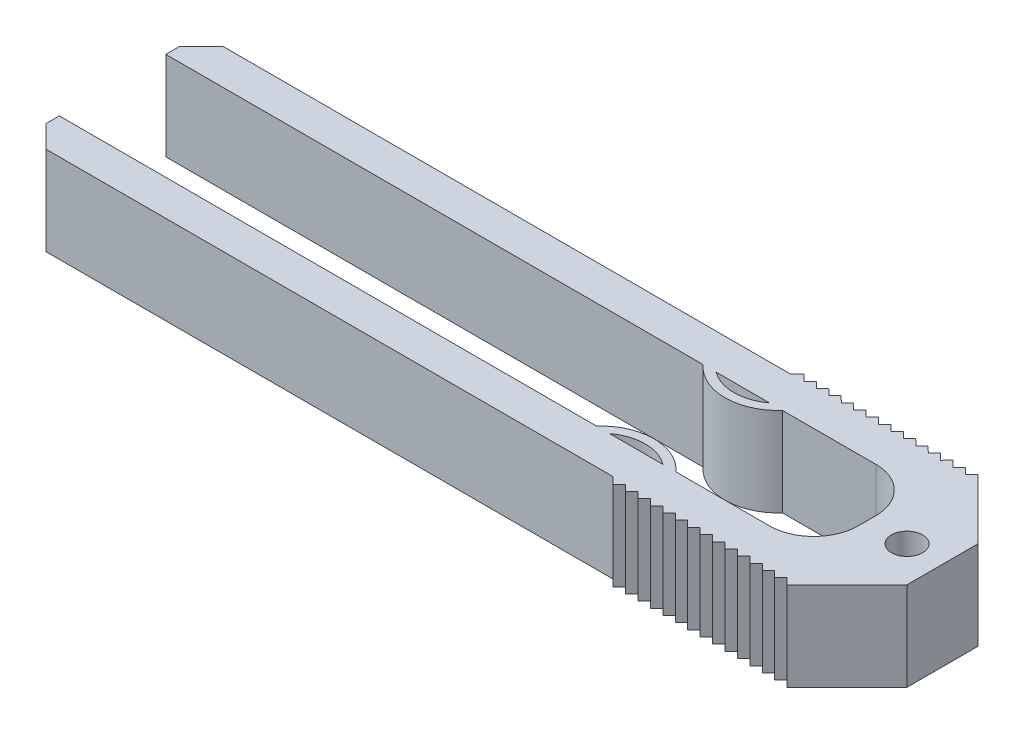
SolidWorks part; units mm, degrees
ref_plane "Front Plane" through (0, 0, 0) normal (0, 0, 1) x (1, 0, 0)
ref_plane "Top Plane" through (0, 0, 0) normal (0, 1, 0) x (1, 0, 0)
ref_plane "Right Plane" through (0, 0, 0) normal (1, 0, 0) x (0, 0, -1)
sketch "Sketch1" plane through (0, 0, 0) normal (0, 1, 0) x (1, 0, 0)
  line L0 (-90, -12) -> (-90, -20)
  line L1 (-90, 20) -> (90, 20)
  line L2 (-90, 20) -> (-90, 12)
  line L3 (-90, -20) -> (90, -20)
  line L4 (90, 20) -> (90, -20)
  line L5 (-90, 20) -> (90, -20) construction
  line L6 (-90, -20) -> (90, 20) construction
  line L7 (-90, 12) -> (80, 12)
  line L9 (-90, -12) -> (80, -12)
  line L10 (80, 12) -> (80, -12)
  point P0 (0, 0)
  dimension "D1" = 180
  dimension "D2" = 24
  dimension "D3" = 8
  dimension "D4" = 8
  dimension "D5" = 10
extrude "Boss-Extrude1" add sketch "Sketch1" along normal blind 20
fillet "Fillet1" radius 10 2 edges at (80, 10, 12) (80, 10, -12)
chamfer "Chamfer1" distance 5 angle 45 2 edges at (90, 10, 20) (90, 10, -20)
chamfer "Chamfer2" distance 5 angle 45 2 edges at (-90, 10, -20) (-90, 10, 20)
sketch "Sketch2" plane through (0, 20, 0) normal (0, 1, 0) x (1, 0, 0)
  line L0 (85, 20) -> (-85, 20) construction
  line L1 (-85, -20) -> (85, -20) construction
  line L2 (80, 2) -> (80, -2) construction
  line L3 (31.0557, -12) -> (34, -12)
  line L4 (70, -12) -> (-90, -12) construction
  line L5 (31.0557, 12) -> (34, 12)
  line L6 (-90, 12) -> (70, 12) construction
  line L7 (46, -12) -> (48.9443, -12)
  line L8 (46, 12) -> (48.9443, 12)
  arc A0 (31.0557, 12) -> (48.9443, 12) centre (40, 20) ccw
  arc A1 (48.9443, -12) -> (31.0557, -12) centre (40, -20) ccw
  arc A2 (34, 12) -> (46, 12) centre (40, 20) ccw
  arc A3 (46, -12) -> (34, -12) centre (40, -20) ccw
  dimension "D1" = 24
  dimension "D2" = 24
  dimension "D3" = 40
  dimension "D4" = 40
  dimension "D5" = 2
  dimension "D6" = 2
extrude "Boss-Extrude2" add sketch "Sketch2" against normal blind 20
sketch "Sketch3" plane through (0, 20, 0) normal (0, 1, 0) x (1, 0, 0)
  line L0 (85, 20) -> (83.4689, 21.5)
  line L1 (83.4689, 21.5) -> (81.9994, 20)
  line L2 (85, 20) -> (-85, 20) construction
  line L3 (81.9994, 20) -> (85, 20)
  line L4 (80.6689, 21.5) -> (79.1994, 20)
  line L5 (79.1994, 20) -> (82.2, 20)
  line L6 (82.2, 20) -> (80.6689, 21.5)
  line L7 (77.8689, 21.5) -> (76.3994, 20)
  line L8 (76.3994, 20) -> (79.4, 20)
  line L9 (79.4, 20) -> (77.8689, 21.5)
  line L10 (75.0689, 21.5) -> (73.5994, 20)
  line L11 (73.5994, 20) -> (76.6, 20)
  line L12 (76.6, 20) -> (75.0689, 21.5)
  line L13 (72.2689, 21.5) -> (70.7994, 20)
  line L14 (70.7994, 20) -> (73.8, 20)
  line L15 (73.8, 20) -> (72.2689, 21.5)
  line L16 (69.4689, 21.5) -> (67.9994, 20)
  line L17 (67.9994, 20) -> (71, 20)
  line L18 (71, 20) -> (69.4689, 21.5)
  line L19 (66.6689, 21.5) -> (65.1994, 20)
  line L20 (65.1994, 20) -> (68.2, 20)
  line L21 (68.2, 20) -> (66.6689, 21.5)
  line L22 (63.8689, 21.5) -> (62.3994, 20)
  line L23 (62.3994, 20) -> (65.4, 20)
  line L24 (65.4, 20) -> (63.8689, 21.5)
  line L25 (61.0689, 21.5) -> (59.5994, 20)
  line L26 (59.5994, 20) -> (62.6, 20)
  line L27 (62.6, 20) -> (61.0689, 21.5)
  line L28 (58.2689, 21.5) -> (56.7994, 20)
  line L29 (56.7994, 20) -> (59.8, 20)
  line L30 (59.8, 20) -> (58.2689, 21.5)
  line L31 (55.4689, 21.5) -> (53.9994, 20)
  line L32 (53.9994, 20) -> (57, 20)
  line L33 (57, 20) -> (55.4689, 21.5)
  line L34 (52.6689, 21.5) -> (51.1994, 20)
  line L35 (51.1994, 20) -> (54.2, 20)
  line L36 (54.2, 20) -> (52.6689, 21.5)
  line L37 (49.8689, 21.5) -> (48.3994, 20)
  line L38 (48.3994, 20) -> (51.4, 20)
  line L39 (51.4, 20) -> (49.8689, 21.5)
  line L40 (47.0689, 21.5) -> (45.5994, 20)
  line L41 (45.5994, 20) -> (48.6, 20)
  line L42 (48.6, 20) -> (47.0689, 21.5)
  line L43 (44.2689, 21.5) -> (42.7994, 20)
  line L44 (42.7994, 20) -> (45.8, 20)
  line L45 (45.8, 20) -> (44.2689, 21.5)
  line M6 (85, 20) -> (-85, 20)
  dimension "D1" = 1.5
  dimension "D2" = 15
extrude "Boss-Extrude3" add sketch "Sketch3" against normal blind 20 contours L6 L0 L1 M6 | L9 L1 L6 L4 M6 | L12 L4 L9 L7 M6 | L15 L7 L12 L10 M6 | L18 L10 L15 L13 M6 | L21 L13 L18 L16 M6 | L24 L16 L21 L19 M6 | L27 L19 L24 L22 M6 | L30 L22 L27 L25 M6 | L33 L25 L30 L28 M6 | L36 L28 L33 L31 M6 | L40 L45 L43 M6 | L45 L37 L42 L40 M6 | L42 L34 L39 L37 M6 | L39 L31 L36 L34 M6 | L41 L45 L40 | L38 L42 L37 | L35 L39 L34 | L32 L36 L31 | L29 L33 L28 | L26 L30 L25 | L23 L27 L22 | L20 L24 L19 | L17 L21 L16 | L14 L18 L13 | L11 L15 L10
sketch "Sketch4" plane through (0, 20, 0) normal (0, 1, 0) x (1, 0, 0)
  line L0 (85, -20) -> (83.5, -21.5)
  line L1 (83.5, -21.5) -> (82, -20)
  line L2 (-85, -20) -> (85, -20) construction
  line L3 (82, -20) -> (85, -20)
  line L4 (80.7, -21.5) -> (79.2, -20)
  line L5 (82.2, -20) -> (80.7, -21.5)
  line L6 (79.2, -20) -> (82.2, -20)
  line L7 (77.9, -21.5) -> (76.4, -20)
  line L8 (79.4, -20) -> (77.9, -21.5)
  line L9 (76.4, -20) -> (79.4, -20)
  line L10 (75.1, -21.5) -> (73.6, -20)
  line L11 (76.6, -20) -> (75.1, -21.5)
  line L12 (73.6, -20) -> (76.6, -20)
  line L13 (72.3, -21.5) -> (70.8, -20)
  line L14 (73.8, -20) -> (72.3, -21.5)
  line L15 (70.8, -20) -> (73.8, -20)
  line L16 (69.5, -21.5) -> (68, -20)
  line L17 (71, -20) -> (69.5, -21.5)
  line L18 (68, -20) -> (71, -20)
  line L19 (66.7, -21.5) -> (65.2, -20)
  line L20 (68.2, -20) -> (66.7, -21.5)
  line L21 (65.2, -20) -> (68.2, -20)
  line L22 (63.9, -21.5) -> (62.4, -20)
  line L23 (65.4, -20) -> (63.9, -21.5)
  line L24 (62.4, -20) -> (65.4, -20)
  line L25 (61.1, -21.5) -> (59.6, -20)
  line L26 (62.6, -20) -> (61.1, -21.5)
  line L27 (59.6, -20) -> (62.6, -20)
  line L28 (58.3, -21.5) -> (56.8, -20)
  line L29 (59.8, -20) -> (58.3, -21.5)
  line L30 (56.8, -20) -> (59.8, -20)
  line L31 (55.5, -21.5) -> (54, -20)
  line L32 (57, -20) -> (55.5, -21.5)
  line L33 (54, -20) -> (57, -20)
  line L34 (52.7, -21.5) -> (51.2, -20)
  line L35 (54.2, -20) -> (52.7, -21.5)
  line L36 (51.2, -20) -> (54.2, -20)
  line L37 (49.9, -21.5) -> (48.4, -20)
  line L38 (51.4, -20) -> (49.9, -21.5)
  line L39 (48.4, -20) -> (51.4, -20)
  line L40 (47.1, -21.5) -> (45.6, -20)
  line L41 (48.6, -20) -> (47.1, -21.5)
  line L42 (45.6, -20) -> (48.6, -20)
  line L43 (44.3, -21.5) -> (42.8, -20)
  line L44 (45.8, -20) -> (44.3, -21.5)
  line L45 (42.8, -20) -> (45.8, -20)
  dimension "D1" = 1.5
  dimension "D2" = 45
  dimension "D3" = 15
extrude "Boss-Extrude4" add sketch "Sketch4" against normal blind 20 contours L3 L5 L1 L0 | L5 L3 L1 | L6 L8 L4 L5 L1 | L8 L6 L4 | L9 L11 L7 L8 L4 | L12 L14 L10 L11 L7 | L11 L9 L7 | L14 L12 L10 | L15 L17 L13 L14 L10 | L17 L15 L13 | L18 L20 L16 L17 L13 | L21 L23 L19 L20 L16 | L24 L26 L22 L23 L19 | L26 L24 L22 | L27 L29 L25 L26 L22 | L33 L35 L31 L32 L28 | L30 L32 L28 L29 L25 | L32 L30 L28 | L29 L27 L25 | L36 L38 L34 L35 L31 | L39 L41 L37 L38 L34 | L42 L44 L40 L41 L37 | L45 L43 L44 L40 | L38 L36 L34 | L35 L33 L31
sketch "Sketch5" plane through (0, 20, 0) normal (0, 1, 0) x (1, 0, 0)
  line L0 (90, 15) -> (97, 8)
  line L1 (90, -15) -> (97, -8)
  line L2 (97, -8) -> (97, 8)
  line L3 (90, -15) -> (90, 15) construction
  line L4 (90, 15) -> (90, -15)
  line L77 (90, 15) -> (85, 20)
  line L78 (85, 20) -> (83.4689, 21.5)
  line L79 (83.4689, 21.5) -> (82.0976, 20.1003)
  line L80 (82.0976, 20.1003) -> (80.6689, 21.5)
  line L81 (80.6689, 21.5) -> (79.2976, 20.1003)
  line L82 (79.2976, 20.1003) -> (77.8689, 21.5)
  line L83 (77.8689, 21.5) -> (76.4976, 20.1003)
  line L84 (76.4976, 20.1003) -> (75.0689, 21.5)
  line L85 (75.0689, 21.5) -> (73.6976, 20.1003)
  line L86 (73.6976, 20.1003) -> (72.2689, 21.5)
  line L87 (72.2689, 21.5) -> (70.8976, 20.1003)
  line L88 (70.8976, 20.1003) -> (69.4689, 21.5)
  line L89 (69.4689, 21.5) -> (68.0976, 20.1003)
  line L90 (68.0976, 20.1003) -> (66.6689, 21.5)
  line L91 (66.6689, 21.5) -> (65.2976, 20.1003)
  line L92 (65.2976, 20.1003) -> (63.8689, 21.5)
  line L93 (63.8689, 21.5) -> (62.4976, 20.1003)
  line L94 (62.4976, 20.1003) -> (61.0689, 21.5)
  line L95 (61.0689, 21.5) -> (59.6976, 20.1003)
  line L96 (59.6976, 20.1003) -> (58.2689, 21.5)
  line L97 (58.2689, 21.5) -> (56.8976, 20.1003)
  line L98 (56.8976, 20.1003) -> (55.4689, 21.5)
  line L99 (55.4689, 21.5) -> (54.0976, 20.1003)
  line L100 (54.0976, 20.1003) -> (52.6689, 21.5)
  line L101 (52.6689, 21.5) -> (51.2976, 20.1003)
  line L102 (51.2976, 20.1003) -> (49.8689, 21.5)
  line L103 (49.8689, 21.5) -> (48.4976, 20.1003)
  line L104 (48.4976, 20.1003) -> (47.0689, 21.5)
  line L105 (47.0689, 21.5) -> (45.6976, 20.1003)
  line L106 (45.6976, 20.1003) -> (44.2689, 21.5)
  line L107 (44.2689, 21.5) -> (42.7994, 20)
  line L108 (42.7994, 20) -> (-85, 20)
  line L109 (-85, 20) -> (-90, 15)
  line L110 (-90, 15) -> (-90, 12)
  line L111 (-90, 12) -> (31.0557, 12)
  line L112 (48.9443, 12) -> (70, 12)
  line L113 (80, 2) -> (80, -2)
  line L114 (70, -12) -> (48.9443, -12)
  line L115 (31.0557, -12) -> (-90, -12)
  line L116 (-90, -12) -> (-90, -15)
  line L117 (-90, -15) -> (-85, -20)
  line L118 (-85, -20) -> (42.8, -20)
  line L119 (42.8, -20) -> (44.3, -21.5)
  line L120 (44.3, -21.5) -> (45.7, -20.1)
  line L121 (45.7, -20.1) -> (47.1, -21.5)
  line L122 (47.1, -21.5) -> (48.5, -20.1)
  line L123 (48.5, -20.1) -> (49.9, -21.5)
  line L124 (49.9, -21.5) -> (51.3, -20.1)
  line L125 (51.3, -20.1) -> (52.7, -21.5)
  line L126 (52.7, -21.5) -> (54.1, -20.1)
  line L127 (54.1, -20.1) -> (55.5, -21.5)
  line L128 (55.5, -21.5) -> (56.9, -20.1)
  line L129 (56.9, -20.1) -> (58.3, -21.5)
  line L130 (58.3, -21.5) -> (59.7, -20.1)
  line L131 (59.7, -20.1) -> (61.1, -21.5)
  line L132 (61.1, -21.5) -> (62.5, -20.1)
  line L133 (62.5, -20.1) -> (63.9, -21.5)
  line L134 (63.9, -21.5) -> (65.3, -20.1)
  line L135 (65.3, -20.1) -> (66.7, -21.5)
  line L136 (66.7, -21.5) -> (68.1, -20.1)
  line L137 (68.1, -20.1) -> (69.5, -21.5)
  line L138 (69.5, -21.5) -> (70.9, -20.1)
  line L139 (70.9, -20.1) -> (72.3, -21.5)
  line L140 (72.3, -21.5) -> (73.7, -20.1)
  line L141 (73.7, -20.1) -> (75.1, -21.5)
  line L142 (75.1, -21.5) -> (76.5, -20.1)
  line L143 (76.5, -20.1) -> (77.9, -21.5)
  line L144 (77.9, -21.5) -> (79.3, -20.1)
  line L145 (79.3, -20.1) -> (80.7, -21.5)
  line L146 (80.7, -21.5) -> (82.1, -20.1)
  line L147 (82.1, -20.1) -> (83.5, -21.5)
  line L148 (83.5, -21.5) -> (90, -15)
  line L149 (90, -15) -> (90, 15)
  line L150 (90, 15) -> (85, 20)
  line L151 (85, 20) -> (83.4689, 21.5)
  line L152 (83.4689, 21.5) -> (82.0976, 20.1003)
  line L153 (82.0976, 20.1003) -> (80.6689, 21.5)
  line L154 (80.6689, 21.5) -> (79.2976, 20.1003)
  line L155 (79.2976, 20.1003) -> (77.8689, 21.5)
  line L156 (77.8689, 21.5) -> (76.4976, 20.1003)
  line L157 (76.4976, 20.1003) -> (75.0689, 21.5)
  line L158 (75.0689, 21.5) -> (73.6976, 20.1003)
  line L159 (73.6976, 20.1003) -> (72.2689, 21.5)
  line L160 (72.2689, 21.5) -> (70.8976, 20.1003)
  line L161 (70.8976, 20.1003) -> (69.4689, 21.5)
  line L162 (69.4689, 21.5) -> (68.0976, 20.1003)
  line L163 (68.0976, 20.1003) -> (66.6689, 21.5)
  line L164 (66.6689, 21.5) -> (65.2976, 20.1003)
  line L165 (65.2976, 20.1003) -> (63.8689, 21.5)
  line L166 (63.8689, 21.5) -> (62.4976, 20.1003)
  line L167 (62.4976, 20.1003) -> (61.0689, 21.5)
  line L168 (61.0689, 21.5) -> (59.6976, 20.1003)
  line L169 (59.6976, 20.1003) -> (58.2689, 21.5)
  line L170 (58.2689, 21.5) -> (56.8976, 20.1003)
  line L171 (56.8976, 20.1003) -> (55.4689, 21.5)
  line L172 (55.4689, 21.5) -> (54.0976, 20.1003)
  line L173 (54.0976, 20.1003) -> (52.6689, 21.5)
  line L174 (52.6689, 21.5) -> (51.2976, 20.1003)
  line L175 (51.2976, 20.1003) -> (49.8689, 21.5)
  line L176 (49.8689, 21.5) -> (48.4976, 20.1003)
  line L177 (48.4976, 20.1003) -> (47.0689, 21.5)
  line L178 (47.0689, 21.5) -> (45.6976, 20.1003)
  line L179 (45.6976, 20.1003) -> (44.2689, 21.5)
  line L180 (44.2689, 21.5) -> (42.7994, 20)
  line L181 (42.7994, 20) -> (-85, 20)
  line L182 (-85, 20) -> (-90, 15)
  line L183 (-90, 15) -> (-90, 12)
  line L184 (-90, 12) -> (31.0557, 12)
  line L185 (48.9443, 12) -> (70, 12)
  line L186 (80, 2) -> (80, -2)
  line L187 (70, -12) -> (48.9443, -12)
  line L188 (31.0557, -12) -> (-90, -12)
  line L189 (-90, -12) -> (-90, -15)
  line L190 (-90, -15) -> (-85, -20)
  line L191 (-85, -20) -> (42.8, -20)
  line L192 (42.8, -20) -> (44.3, -21.5)
  line L193 (44.3, -21.5) -> (45.7, -20.1)
  line L194 (45.7, -20.1) -> (47.1, -21.5)
  line L195 (47.1, -21.5) -> (48.5, -20.1)
  line L196 (48.5, -20.1) -> (49.9, -21.5)
  line L197 (49.9, -21.5) -> (51.3, -20.1)
  line L198 (51.3, -20.1) -> (52.7, -21.5)
  line L199 (52.7, -21.5) -> (54.1, -20.1)
  line L200 (54.1, -20.1) -> (55.5, -21.5)
  line L201 (55.5, -21.5) -> (56.9, -20.1)
  line L202 (56.9, -20.1) -> (58.3, -21.5)
  line L203 (58.3, -21.5) -> (59.7, -20.1)
  line L204 (59.7, -20.1) -> (61.1, -21.5)
  line L205 (61.1, -21.5) -> (62.5, -20.1)
  line L206 (62.5, -20.1) -> (63.9, -21.5)
  line L207 (63.9, -21.5) -> (65.3, -20.1)
  line L208 (65.3, -20.1) -> (66.7, -21.5)
  line L209 (66.7, -21.5) -> (68.1, -20.1)
  line L210 (68.1, -20.1) -> (69.5, -21.5)
  line L211 (69.5, -21.5) -> (70.9, -20.1)
  line L212 (70.9, -20.1) -> (72.3, -21.5)
  line L213 (72.3, -21.5) -> (73.7, -20.1)
  line L214 (73.7, -20.1) -> (75.1, -21.5)
  line L215 (75.1, -21.5) -> (76.5, -20.1)
  line L216 (76.5, -20.1) -> (77.9, -21.5)
  line L217 (77.9, -21.5) -> (79.3, -20.1)
  line L218 (79.3, -20.1) -> (80.7, -21.5)
  line L219 (80.7, -21.5) -> (82.1, -20.1)
  line L220 (82.1, -20.1) -> (83.5, -21.5)
  line L221 (83.5, -21.5) -> (90, -15)
  arc A4 (31.0557, 12) -> (48.9443, 12) centre (40, 20) ccw
  arc A5 (80, 2) -> (70, 12) centre (70, 2) ccw
  arc A6 (70, -12) -> (80, -2) centre (70, -2) ccw
  arc A7 (48.9443, -12) -> (31.0557, -12) centre (40, -20) ccw
  arc A8 (31.0557, 12) -> (48.9443, 12) centre (40, 20) ccw
  arc A9 (80, 2) -> (70, 12) centre (70, 2) ccw
  arc A10 (70, -12) -> (80, -2) centre (70, -2) ccw
  arc A11 (48.9443, -12) -> (31.0557, -12) centre (40, -20) ccw
  dimension "D1" = 7
  dimension "D2" = 45
  dimension "D3" = 45
  dimension "D4" = 0
extrude "Boss-Extrude5" add sketch "Sketch5" against normal blind 20 contours L0 L4 L1 L2
sketch "Sketch6" plane through (0, 20, 0) normal (0, 1, 0) x (1, 0, 0)
  line L0 (97, -8) -> (97, 8) construction
  circle A0 centre (89, 0) radius 3.5
  dimension "D1" = 7
  dimension "D2" = 8
extrude "Cut-Extrude1" cut sketch "Sketch6" against normal blind 20
